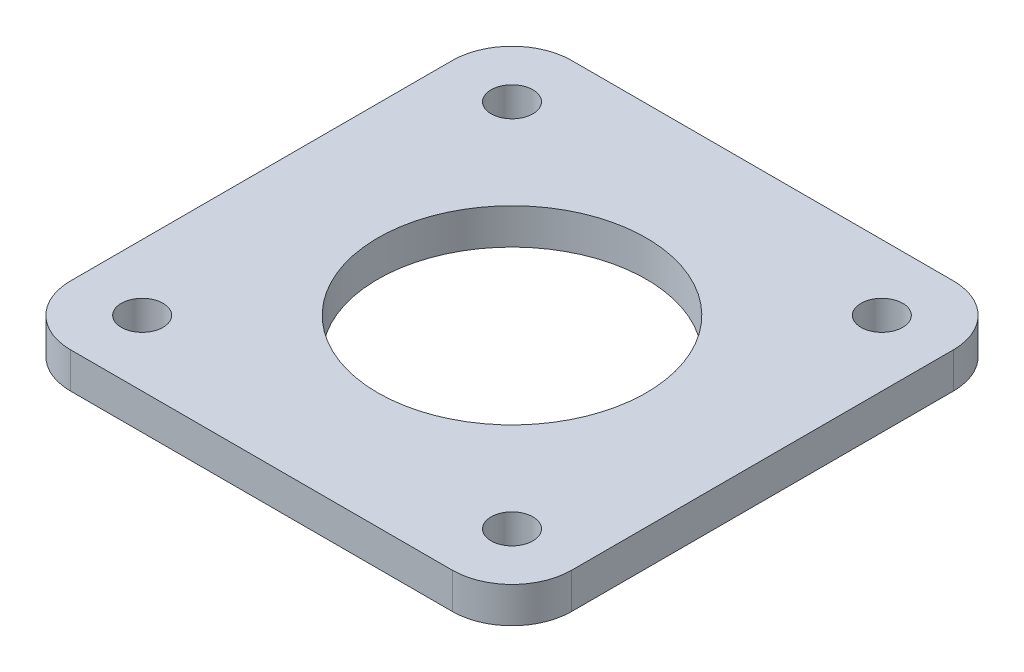
SolidWorks part; units mm, degrees
ref_plane "Front Plane" through (0, 0, 0) normal (0, 0, 1) x (1, 0, 0)
ref_plane "Top Plane" through (0, 0, 0) normal (0, 1, 0) x (1, 0, 0)
ref_plane "Right Plane" through (0, 0, 0) normal (1, 0, 0) x (0, 0, -1)
sketch "Sketch1" plane through (0, 0, 0) normal (0, 1, 0) x (1, 0, 0)
  line L1 (-21, 21) -> (21, 21)
  line L2 (-21, 21) -> (-21, -21)
  line L3 (-21, -21) -> (21, -21)
  line L4 (21, 21) -> (21, -21)
  line L5 (-21, 21) -> (21, -21) construction
  line L6 (-21, -21) -> (21, 21) construction
  point P0 (0, 0)
  dimension "D1" = 42
  dimension "D2" = 42
extrude "Boss-Extrude1" add sketch "Sketch1" along normal blind 3
sketch "Sketch2" plane through (0, 3, 0) normal (0, 1, 0) x (1, 0, 0)
  line L1 (-15.5, 15.5) -> (15.5, 15.5)
  line L2 (-15.5, 15.5) -> (-15.5, -15.5)
  line L3 (-15.5, -15.5) -> (15.5, -15.5)
  line L4 (15.5, 15.5) -> (15.5, -15.5)
  line L5 (-15.5, 15.5) -> (15.5, -15.5) construction
  line L6 (-15.5, -15.5) -> (15.5, 15.5) construction
  circle A0 centre (-15.5, 15.5) radius 1.75
  circle A1 centre (15.5, 15.5) radius 1.75
  circle A2 centre (15.5, -15.5) radius 1.75
  circle A3 centre (-15.5, -15.5) radius 1.75
  circle A4 centre (0, 0) radius 11.25
  point P0 (0, 0)
  dimension "D3" = 3.5
  dimension "D4" = 3.5
  dimension "D5" = 3.5
  dimension "D6" = 3.5
  dimension "D7" = 22.5
  dimension "D1" = 31
  dimension "D2" = 31
extrude "Cut-Extrude1" cut sketch "Sketch2" against normal through all contours A0 | A1 | A4 | A3 | A2
fillet "Fillet1" radius 5 4 edges at (21, 1.5, 21) (21, 1.5, -21) (-21, 1.5, -21) (-21, 1.5, 21)
